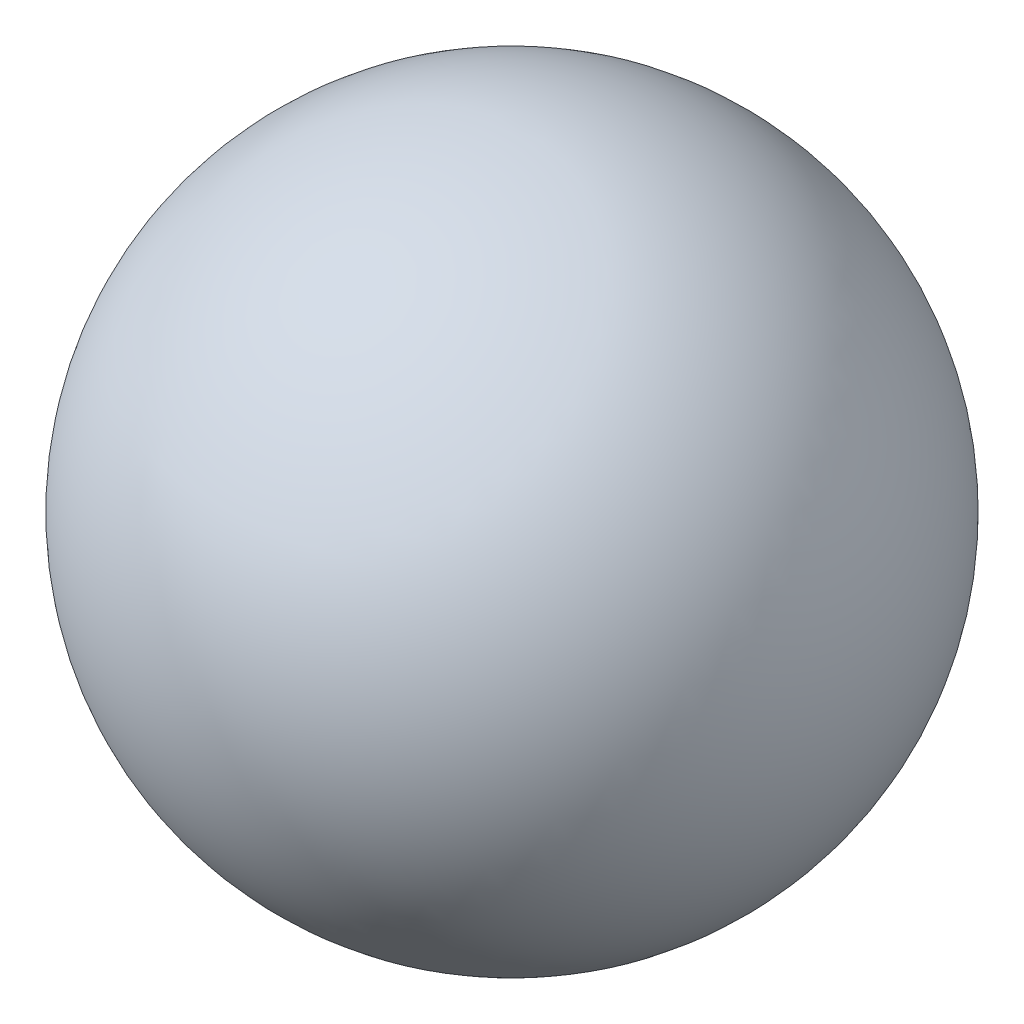
SolidWorks part; units mm, degrees
ref_plane "Front Plane" through (0, 0, 0) normal (0, 0, 1) x (1, 0, 0)
ref_plane "Top Plane" through (0, 0, 0) normal (0, 1, 0) x (1, 0, 0)
ref_plane "Right Plane" through (0, 0, 0) normal (1, 0, 0) x (0, 0, -1)
sketch "Sketch1" plane through (0, 0, 0) normal (0, 0, 1) x (1, 0, 0)
  line L0 (0, -2.525) -> (0, 2.525)
  arc A0 (0, -2.525) -> (0, 2.525) centre (0, 0) ccw
revolve "True_Sphere_D5.05" add sketch "Sketch1" angle 360 about L0
